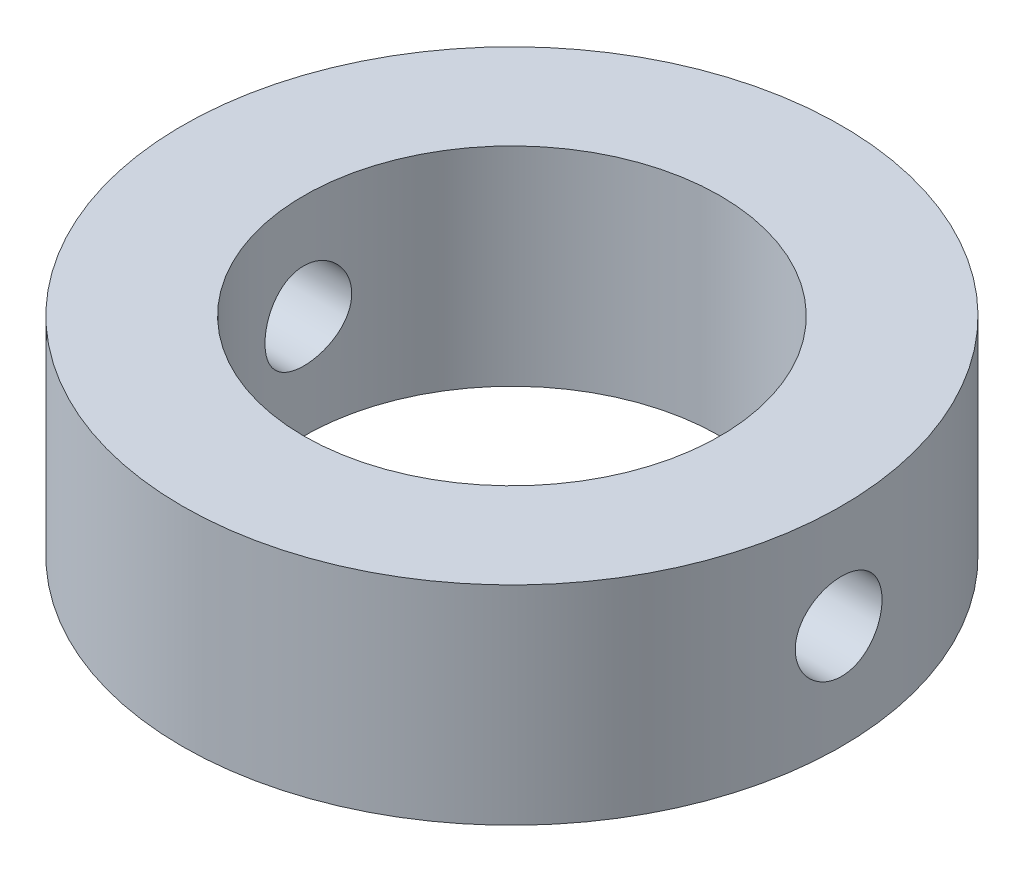
SolidWorks part; units mm, degrees
material "Brass"
ref_plane "Front Plane" through (0, 0, 0) normal (0, 0, 1) x (1, 0, 0)
ref_plane "Top Plane" through (0, 0, 0) normal (0, 1, 0) x (1, 0, 0)
ref_plane "Right Plane" through (0, 0, 0) normal (1, 0, 0) x (0, 0, -1)
sketch "Sketch1" plane through (0, 0, 0) normal (0, 1, 0) x (1, 0, 0)
  circle A0 centre (0, 0) radius 12
  circle A1 centre (0, 0) radius 19
  dimension "D1" = 24
  dimension "D2" = 38
extrude "Boss-Extrude1" add sketch "Sketch1" along normal blind 12
sketch "Sketch5" plane through (0, 0, 0) normal (1, 0, 0) x (0, 0, -1)
  line L0 (0, -1000) -> (0, 49000) construction
  line L1 (-1019, 6) -> (48981, 6) construction
  line L2 (-19, 12) -> (-19, 0) construction
  circle A0 centre (0, 6) radius 2.5
  point P8 (-19, 6)
  dimension "D1" = 5
extrude "Cut-Extrude1" cut sketch "Sketch5" against normal through all both and the other way through all
